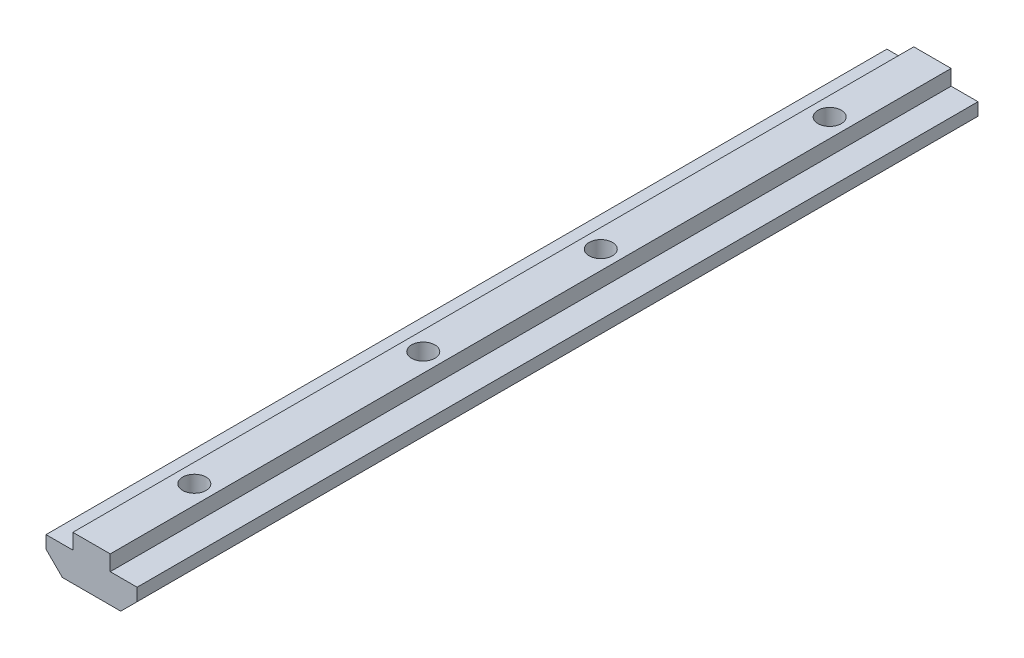
SolidWorks part; units mm, degrees
ref_plane "前视基准面" through (0, 0, 0) normal (0, 0, 1) x (1, 0, 0)
ref_plane "上视基准面" through (0, 0, 0) normal (0, 1, 0) x (1, 0, 0)
ref_plane "右视基准面" through (0, 0, 0) normal (1, 0, 0) x (0, 0, -1)
sketch "草图1" plane through (0, 0, 0) normal (0, 0, 1) x (1, 0, 0)
  line B0 (12.5, 0) -> (0, 0)
  line B1 (2.25, 9.5) -> (10.25, 9.5)
  line B2 (16, 6.2) -> (10.25, 6.2)
  line B3 (2.25, 6.2) -> (-3.5, 6.2)
  line B4 (16, 3.5) -> (16, 6.2)
  line B5 (-3.5, 6.2) -> (-3.5, 3.5)
  line B6 (10.25, 9.5) -> (10.25, 6.2)
  line B7 (2.25, 9.5) -> (2.25, 6.2)
  line B8 (0, 0) -> (-3.5, 3.5)
  line B9 (12.5, 0) -> (16, 3.5)
sketch_block_instance "A$C500F67B3-1"
sketch_block "A$C500F67B3"
extrude "凸台-拉伸1" add sketch "草图1" along normal blind 180
sketch "草图3" plane through (0, 9.5, 0) normal (0, 1, 0) x (1, 0, 0)
  point P0 (6.25, -158)
  point P7 (6.25, -71)
  point P8 (6.25, -109)
  point P9 (6.25, -22)
  dimension "D2" = 2
hole_wizard "M6 螺纹孔1" positions "3D草图1" profile "草图4" tap size "M6" standard "Iso"
sketch3d "3D草图1"
  point P0 (6.25, 9.5, 158)
  point P3 (6.25, 9.5, 109)
  point P6 (6.25, 9.5, 22)
  point P9 (6.25, 9.5, 71)
sketch "草图4" plane through (6.25, 9.5, 158) normal (1, 0, 0) x (0, 0, 1)
  line L0 (0, 0) -> (0, 29.5022)
  line L1 (0, 29.5022) -> (2.5, 28)
  line L2 (2.5, 28) -> (2.5, 0)
  line L5 (2.5, 0) -> (0, 0)
  line L10 (0, 29.5022) -> (-2.5, 28) construction
  line L11 (0, -6.35) -> (0, 107.95) construction
  dimension "螺纹孔钻头直径" = 5
  dimension "螺纹孔钻头深度" = 28
  dimension "导头角度" = 118
cosmetic thread "孔螺蚊线1"
cosmetic thread "孔螺蚊线2"
cosmetic thread "孔螺蚊线3"
cosmetic thread "孔螺蚊线4"
